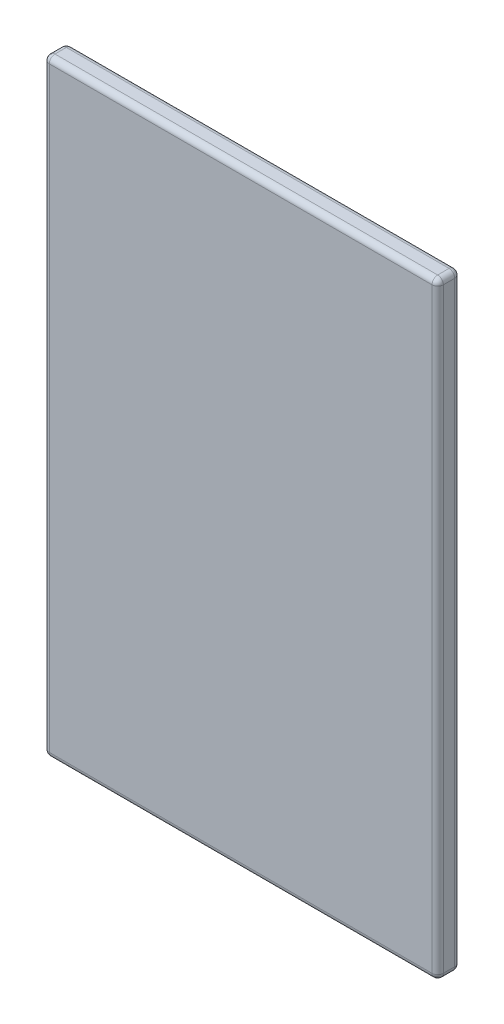
SolidWorks part; units mm, degrees
ref_plane "Front Plane" through (0, 0, 0) normal (0, 0, 1) x (1, 0, 0)
ref_plane "Top Plane" through (0, 0, 0) normal (0, 1, 0) x (1, 0, 0)
ref_plane "Right Plane" through (0, 0, 0) normal (1, 0, 0) x (0, 0, -1)
sketch "Sketch1" plane through (0, 0, 0) normal (0, 0, 1) x (1, 0, 0)
  line L1 (-17.35, -26.75) -> (17.35, -26.75)
  line L2 (-17.35, -26.75) -> (-17.35, 26.75)
  line L3 (-17.35, 26.75) -> (17.35, 26.75)
  line L4 (17.35, -26.75) -> (17.35, 26.75)
  line L5 (-17.35, -26.75) -> (17.35, 26.75) construction
  line L6 (-17.35, 26.75) -> (17.35, -26.75) construction
  point P0 (0, 0)
  dimension "D1" = 34.7
  dimension "D2" = 53.5
extrude "Boss-Extrude1" add sketch "Sketch1" along normal blind 2
fillet "Fillet1" radius 0.5 12 edges at (0, -26.75, 2) (0, -26.75, 0) (-17.35, 0, 2) (-17.35, -26.75, 1) (-17.35, 0, 0) (0, 26.75, 2) (-17.35, 26.75, 1) (0, 26.75, 0) (17.35, -26.75, 1) (17.35, 0, 2) (17.35, 26.75, 1) (17.35, 0, 0)
